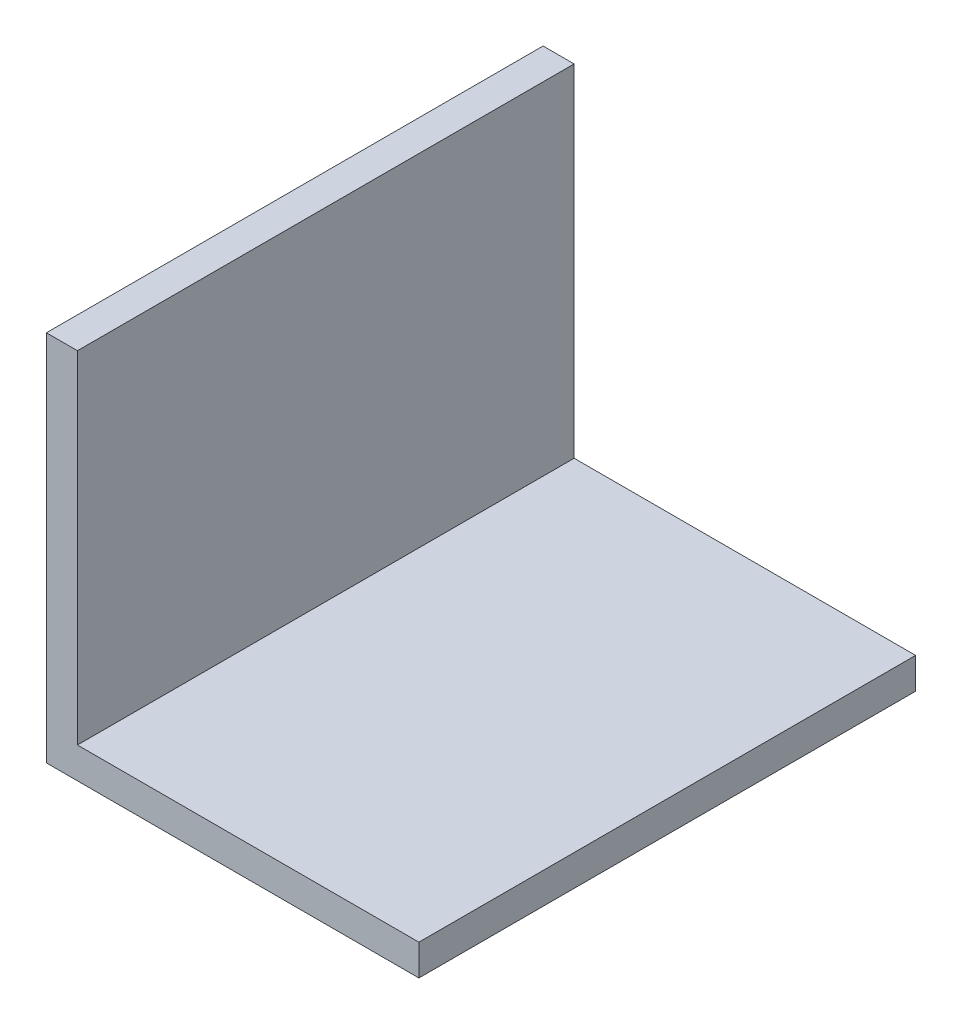
SolidWorks part; units mm, degrees
material "6061 Alloy"
ref_plane "Front Plane" through (0, 0, 0) normal (0, 0, 1) x (1, 0, 0)
ref_plane "Top Plane" through (0, 0, 0) normal (0, 1, 0) x (1, 0, 0)
ref_plane "Right Plane" through (0, 0, 0) normal (1, 0, 0) x (0, 0, -1)
sketch "Sketch1" plane through (0, 0, 0) normal (0, 0, 1) x (1, 0, 0)
  line L0 (0, 0) -> (0, 19.05)
  line L1 (0, 0) -> (19.05, 0)
  line L2 (1.5875, 1.5875) -> (19.05, 1.5875)
  line L3 (1.5875, 1.5875) -> (1.5875, 19.05)
  line L4 (19.05, 1.5875) -> (19.05, 0)
  line L5 (1.5875, 19.05) -> (0, 19.05)
  dimension "D1" = 19.05
  dimension "D2" = 19.05
  dimension "D3" = 1.5875
extrude "Boss-Extrude1" add sketch "Sketch1" along normal blind 25.4
